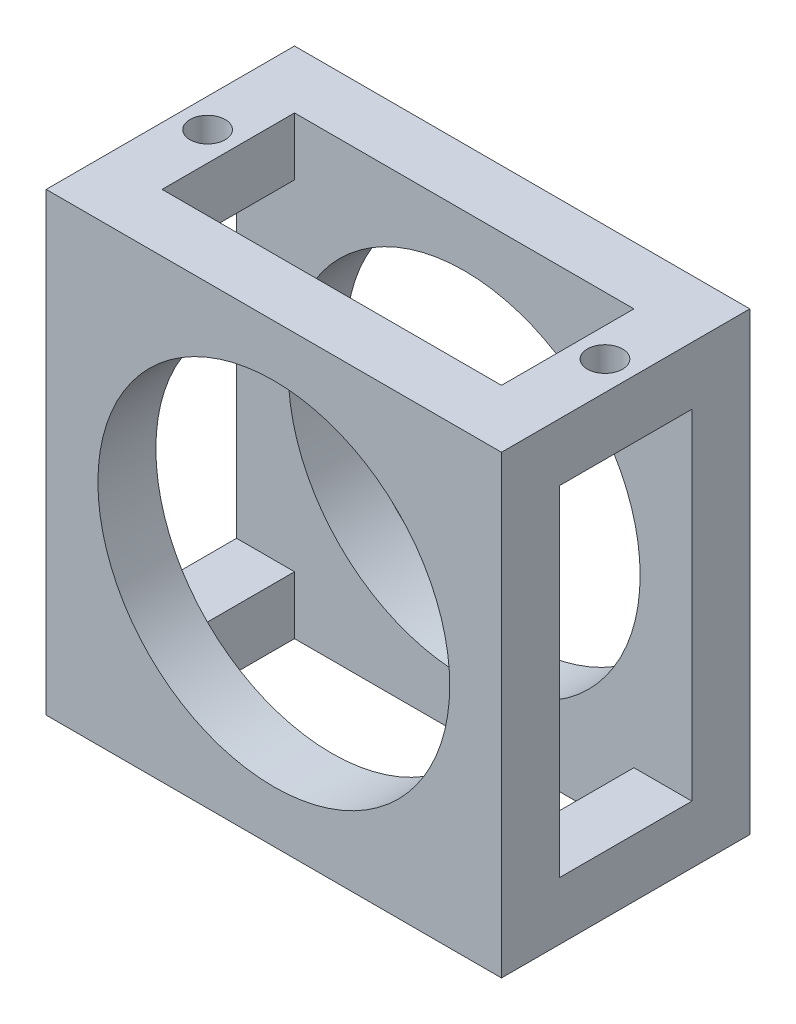
SolidWorks part; units mm, degrees
ref_plane "Front Plane" through (0, 0, 0) normal (0, 0, 1) x (1, 0, 0)
ref_plane "Top Plane" through (0, 0, 0) normal (0, 1, 0) x (1, 0, 0)
ref_plane "Right Plane" through (0, 0, 0) normal (1, 0, 0) x (0, 0, -1)
sketch "Sketch1" plane through (0, 0, 0) normal (0, 0, 1) x (1, 0, 0)
  line L1 (-27.5, 27.5) -> (27.5, 27.5)
  line L2 (-27.5, 27.5) -> (-27.5, -27.5)
  line L3 (-27.5, -27.5) -> (27.5, -27.5)
  line L4 (27.5, 27.5) -> (27.5, -27.5)
  dimension "D1" = 55
  dimension "D2" = 55
  dimension "D3" = 27.5
  dimension "D4" = 27.5
extrude "Boss-Extrude1" add sketch "Sketch1" along normal blind 30
sketch "Sketch2" plane through (0, 0, 30) normal (0, 0, 1) x (1, 0, 0)
  circle A0 centre (0, 0) radius 21.25
  dimension "D1" = 42.5
extrude "Cut-Extrude1" cut sketch "Sketch2" against normal blind 30
sketch "Sketch3" plane through (0, 27.5, 0) normal (0, 1, 0) x (1, 0, 0)
  line L0 (27.5, 0) -> (-27.5, 0) construction
  line L1 (-20.5, -7) -> (20.5, -7)
  line L2 (-20.5, -7) -> (-20.5, -23)
  line L3 (-20.5, -23) -> (20.5, -23)
  line L4 (20.5, -7) -> (20.5, -23)
  line L5 (-27.5, -30) -> (-27.5, 0) construction
  dimension "D1" = 16
  dimension "D2" = 7
  dimension "D3" = 41
  dimension "D4" = 7
extrude "Cut-Extrude2" cut sketch "Sketch3" against normal blind 60
sketch "Sketch4" plane through (27.5, 0, 0) normal (1, 0, 0) x (0, 0, -1)
  line L0 (-30, 27.5) -> (0, 27.5) construction
  line L1 (-23, 20.5) -> (-7, 20.5)
  line L2 (-23, 20.5) -> (-23, -20.5)
  line L3 (-23, -20.5) -> (-7, -20.5)
  line L4 (-7, 20.5) -> (-7, -20.5)
  line L5 (0, -27.5) -> (0, 27.5) construction
  dimension "D1" = 41
  dimension "D2" = 7
  dimension "D3" = 16
  dimension "D4" = 7
extrude "Cut-Extrude3" cut sketch "Sketch4" against normal blind 60
sketch "Sketch5" plane through (0, 27.5, 0) normal (0, 1, 0) x (1, 0, 0)
  line L0 (-20.5, -7) -> (-20.5, -23) construction
  line L1 (20.5, -23) -> (20.5, -7) construction
  line L2 (20.5, -7) -> (-20.5, -7) construction
  circle A0 centre (-24, -14) radius 2.125
  circle A1 centre (24, -14) radius 2.125
  dimension "D1" = 4.25
  dimension "D2" = 4.25
  dimension "D3" = 3.5
  dimension "D4" = 3.5
  dimension "D5" = 7
extrude "Cut-Extrude4" cut sketch "Sketch5" against normal blind 10
